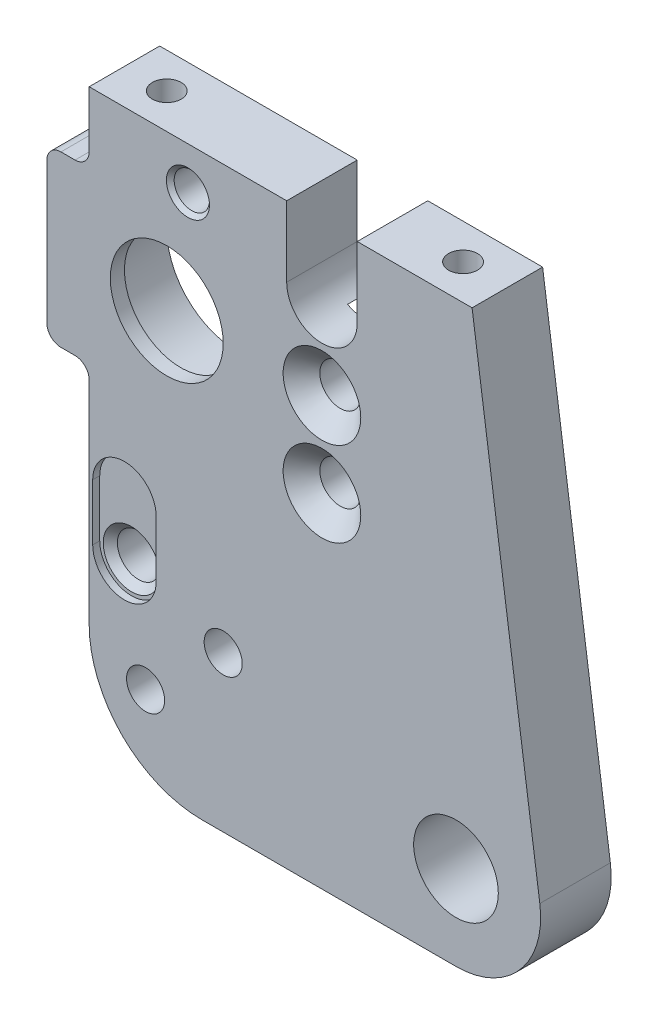
SolidWorks part; units mm, degrees
material "7075-T6, Plate (SS)"
ref_plane "前视基准面" through (0, 0, 0) normal (0, 0, 1) x (1, 0, 0)
ref_plane "上视基准面" through (0, 0, 0) normal (0, 1, 0) x (1, 0, 0)
ref_plane "右视基准面" through (0, 0, 0) normal (1, 0, 0) x (0, 0, -1)
sketch "草图1" plane through (0, 0, 0) normal (0, 0, 1) x (1, 0, 0)
  line L1 (0, 41) -> (34, 41)
  line L2 (0, 41) -> (0, 0)
  line L3 (0, 0) -> (34, 0)
  line L4 (34, 41) -> (34, 0)
  dimension "D1" = 34
  dimension "D2" = 41
  dimension "D3" = 90
extrude "拉伸1" add sketch "草图1" along normal blind 5
fillet "圆角1" radius 8 1 edges at (0, 0, 2.5)
sketch "草图2" plane through (0, 0, 5) normal (0, 0, 1) x (1, 0, 0)
  line L0 (0, 41) -> (0, 8) construction
  line L2 (8, 0) -> (34, 0) construction
  circle A0 centre (26, 6) radius 3
  dimension "D2" = 6
  dimension "D3" = 6
  dimension "D1" = 26
extrude "拉伸2" cut sketch "草图2" against normal up to surface (5 mm away) up to face at (14.8686, 17.6686, 0)
sketch "草图3" plane through (0, 0, 0) normal (0, 0, -1) x (-1, 0, 0)
  line L1 (0, 41) -> (0, 8) construction
  line L2 (-8, 0) -> (-34, 0) construction
  circle A0 centre (-5.5, 30) radius 4
  dimension "D1" = 8
  dimension "D3" = 5.5
  dimension "D2" = 30
extrude "拉伸3" cut sketch "草图3" against normal up to surface (5 mm away) up to face at (29, 6, 5)
sketch "草图4" plane through (0, 0, 0) normal (0, 0, -1) x (-1, 0, 0)
  circle A0 centre (-5.5, 30) radius 5
  dimension "D1" = 10
extrude "拉伸4" cut sketch "草图4" against normal blind 4
sketch "草图5" plane through (0, 41, 0) normal (0, 1, 0) x (1, 0, 0)
  line L0 (3, -2.5) -> (24, -2.5)
  line L1 (17, 0) -> (17, -2.5) construction
  line L2 (34, 0) -> (0, 0) construction
  line L3 (0, -5) -> (0, 0) construction
  dimension "D1" = 21
  dimension "D2" = 2.5
  dimension "D3" = 3
hole_wizard "M2.5 螺纹孔1" positions "3D草图1" profile "草图6" tap size "M2.5" standard "GB"
sketch3d "3D草图1"
  point P0 (3, 41, 2.5)
  point P3 (24, 41, 2.5)
sketch "草图6" plane through (3, 41, 2.5) normal (1, 0, 0) x (0, 0, 1)
  line L0 (0, 0) -> (0, 7.9659)
  line L1 (0, 7.9659) -> (1.025, 7.35)
  line L2 (1.025, 7.35) -> (1.025, 0)
  line L5 (1.025, 0) -> (0, 0)
  line L10 (0, 7.9659) -> (-1.025, 7.35) construction
  line L11 (0, -6.35) -> (0, 107.95) construction
  dimension "螺纹孔钻头直径" = 2.05
  dimension "螺纹孔钻头深度" = 7.35
  dimension "导头角度" = 118
cosmetic thread "孔螺蚊线1" parameters "D1"=6, "D2"=2.5
cosmetic thread "孔螺蚊线2" parameters "D1"=6, "D2"=2.5
chamfer "倒角1" [suppressed] distance 0.5 angle 45
chamfer "倒角2" [suppressed] distance 0.5 angle 45
sketch "草图7" plane through (0, 0, 0) normal (0, 0, -1) x (-1, 0, 0)
  line L0 (-8, 0) -> (-34, 0) construction
  line L1 (-26, 0) -> (-34, 0)
  line L2 (-31.9416, 6.835) -> (-27.14, 41)
  line L3 (-34, 41) -> (0, 41) construction
  line L4 (-34, 0) -> (-34, 41)
  line L5 (-34, 41) -> (-27.14, 41)
  arc A0 (-31.9416, 6.835) -> (-26, 0) centre (-26, 6) ccw
  dimension "D1" = 6
  dimension "D2" = 8
extrude "拉伸5" cut sketch "草图7" against normal blind 10
sketch "Sketch1" plane through (0, 0, 5) normal (0, 0, 1) x (1, 0, 0)
  line L0 (26, 0) -> (12, 0)
  line L1 (8, 0) -> (26, 0) construction
  line L2 (0, 12.9802) -> (0, 12)
  line L3 (0, 41) -> (0, 8) construction
  line L4 (26, 6) -> (29.4415, 1.0851) construction
  line L5 (29.4415, 1.0851) -> (0, 12.9802)
  arc A0 (26, 0) -> (31.9416, 6.835) centre (26, 6) ccw construction
  arc A1 (26, 0) -> (29.4415, 1.0851) centre (26, 6) ccw
  arc A2 (12, 0) -> (0, 12) centre (12, 12) cw
  dimension "D2" = 12
  dimension "D1" = 0
  dimension "D3" = 55
  dimension "D4" = 22
extrude "Extrude1" add sketch "Sketch1" against normal up to surface (5 mm away) up to face at (0.5, 30, 0)
sketch "草图8" plane through (0, 0, 5) normal (0, 0, 1) x (1, 0, 0)
  line L0 (8, 0) -> (26, 0) construction
  line L1 (0, 41) -> (0, 8) construction
  circle A0 centre (2.5, 13) radius 1.5
  dimension "D1" = 3
  dimension "D3" = 2.5
  dimension "D2" = 13
extrude "拉伸6" cut sketch "草图8" against normal blind 4.5
sketch "Sketch9" plane through (0, 0, 0.5) normal (0, 0, 1) x (1, 0, 0)
  line L0 (2.5, 13) -> (1.5, 13) construction
  circle A0 centre (1.5, 13) radius 0.5
  dimension "D2" = 1
  dimension "D1" = 1
extrude "Extrude5" cut sketch "Sketch9" against normal through all
sketch "草图9" plane through (0, 0, 5) normal (0, 0, 1) x (1, 0, 0)
  line L0 (2.5, 13) -> (2.5, 17) construction
  line L1 (0.25, 13) -> (0.25, 17)
  line L2 (4.75, 13) -> (4.75, 17)
  line L3 (0, 41) -> (0, 8) construction
  arc A0 (0.25, 13) -> (4.75, 13) centre (2.5, 13) ccw
  arc A1 (4.75, 17) -> (0.25, 17) centre (2.5, 17) ccw
  point P3 (2.5, 15)
  dimension "D1" = 0
  dimension "D2" = 4.5
  dimension "D3" = 4
extrude "拉伸7" cut sketch "草图9" against normal blind 0.5
chamfer "倒角3" distance 0.5 angle 45 1 edges at (4, 13, 4.5)
sketch "草图11" plane through (0, 0, 5) normal (0, 0, 1) x (1, 0, 0)
  line L0 (4, 19) -> (4, 7)
  line L2 (0, 41) -> (0, 8) construction
  line L3 (2.5, 13) -> (4, 13)
  line L4 (4, 13) -> (9.5, 13)
  dimension "D1" = 12
  dimension "D2" = 5.5
  dimension "D3" = 4
hole_wizard "M2.5 Tapped Hole1" [suppressed] positions "3D草图2" profile "草图12" tap size "M2.5" standard "GB"
sketch3d "3D草图2"
  point P3 (4, -31.5, 5)
  point P6 (9.5, -25.5, 5)
sketch "草图12" plane through (4, -31.5, 5) normal (1, 0, 0) x (0, -1, 0)
  line L0 (0, 0) -> (0, 6.9659)
  line L1 (0, 6.9659) -> (1.025, 6.35)
  line L2 (1.025, 6.35) -> (1.025, 0)
  line L5 (1.025, 0) -> (0, 0)
  line L10 (0, 6.9659) -> (-1.025, 6.35) construction
  line L11 (0, -6.35) -> (0, 107.95) construction
  dimension "螺纹孔钻头直径" = 2.05
  dimension "螺纹孔钻头深度" = 6.35
  dimension "导头角度" = 118
cosmetic thread "孔螺蚊线3" [suppressed] parameters "D1"=5, "D2"=2.5
cosmetic thread "孔螺蚊线4" [suppressed] parameters "D1"=5, "D2"=2.5
chamfer "倒角4" [suppressed] distance 0.2 angle 45
sketch "草图13" plane through (0, 0, 5) normal (0, 0, 1) x (1, 0, 0)
  line L0 (27.14, 41) -> (0, 41) construction
  line L1 (0, 41) -> (0, 8) construction
  circle A0 centre (20, 27) radius 4 construction
  circle A1 centre (16, 12.5) radius 4
  dimension "D1" = 8
  dimension "D2" = 14
  dimension "D3" = 20
  dimension "D4" = 16
  dimension "D5" = 28.5
sketch "Sketch2" plane through (0, 0, 0) normal (0, 0, -1) x (-1, 0, 0)
  line L1 (-13.5, 21.8) -> (-19.5, 21.8)
  line L2 (-13.5, 21.8) -> (-13.5, 33.8)
  line L3 (-13.5, 33.8) -> (-19.5, 33.8)
  line L4 (-19.5, 21.8) -> (-19.5, 33.8)
  line L6 (-16.5, 33.8) -> (-16.5, 21.8) construction
  line L7 (-19.5, 27.8) -> (-13.5, 27.8) construction
  circle A0 centre (-5.5, 30) radius 5 construction
  circle A1 centre (-5.5, 30) radius 5 construction
  dimension "D1" = 11
  dimension "D2" = 2.2
  dimension "D3" = 12
  dimension "D4" = 6
extrude "Extrude2" cut sketch "Sketch2" against normal blind 2
sketch "Sketch3" plane through (0, 0, 5) normal (0, 0, 1) x (1, 0, 0)
  line L0 (13.5, 33.8) -> (19.5, 33.8) construction
  line L1 (13.5, 33.8) -> (19.5, 33.8)
  line L2 (19.5, 21.8) -> (13.5, 21.8) construction
  line L3 (19.5, 21.8) -> (13.5, 21.8)
  line L4 (16.5, 33.8) -> (16.5, 30.3)
  line L5 (16.5, 30.3) -> (16.5, 24.3)
  line L6 (16.5, 24.3) -> (16.5, 21.8)
  dimension "D2" = 2.5
  dimension "D1" = 6
sketch "Sketch7" plane through (0, 0, 0) normal (0, 0, -1) x (-1, 0, 0)
  line L0 (-19.5, 33.8) -> (-19.5, 21.8) construction
  line L1 (-13.5, 21.8) -> (-13.5, 33.8) construction
  circle A0 centre (-19.5, 32.3) radius 1.5
  circle A1 centre (-13.5, 32.3) radius 1.5
  circle A2 centre (-19.5, 23.3) radius 1.5
  circle A3 centre (-13.5, 23.3) radius 1.5
  dimension "D1" = 3
extrude "Extrude3" cut sketch "Sketch7" against normal up to surface (2 mm away) up to face at (16.5, 27.8, 2)
sketch "Sketch8" plane through (0, 0, 0) normal (0, 0, -1) x (-1, 0, 0)
  line L0 (-14, 36) -> (-14, 41)
  line L1 (-27.14, 41) -> (0, 41) construction
  line L2 (-14, 41) -> (-19, 41)
  line L3 (-19, 41) -> (-19, 36)
  line L4 (0, 41) -> (0, 8) construction
  arc A0 (-19, 36) -> (-14, 36) centre (-16.5, 36) ccw
  dimension "D1" = 2.5
  dimension "D2" = 5
  dimension "D3" = 16.5
extrude "Extrude4" cut sketch "Sketch8" against normal through all
sketch "Sketch10" plane through (0, 0, 4.5) normal (0, 0, 1) x (1, 0, 0)
  circle A0 centre (2.5, 13) radius 1.5 construction
  circle A1 centre (2.5, 13) radius 1.5
extrude "Extrude6" cut sketch "Sketch10" against normal blind 10
sketch "Sketch11" plane through (0, 0, 0) normal (0, 0, 1) x (1, 0, 0)
  line L0 (4, 7) -> (4, 6)
  line L1 (4, 13) -> (9.5, 13) construction
  line L2 (4, 11) -> (9.5, 11)
  line L3 (4, 19) -> (4, 7) construction
  dimension "D1" = 7
  dimension "D2" = 5.5
  dimension "D3" = 5
hole_wizard "CBORE for M2.5 Hexagon socket head cap screws1" positions "3DSketch4" profile "Sketch12" counterbore size "M2.5" standard "GB" end condition through all
sketch3d "3DSketch4"
  point P0 (4, 6, 0)
  point P3 (9.5, 11, 0)
sketch "Sketch12" plane through (4, 6, 0) normal (1, 0, 0) x (0, 1, 0)
  line L0 (0, 0) -> (0, 5)
  line L1 (0, 5) -> (1.35, 5)
  line L3 (1.35, 5) -> (1.35, 2.5)
  line L4 (1.35, 2.5) -> (2.5, 2.5)
  line L5 (2.5, 2.5) -> (2.5, 0)
  line L7 (2.5, 0) -> (0, 0)
  line L11 (0, -6.35) -> (0, 107.95) construction
  dimension "Thru Hole Dia." = 2.7
  dimension "Thru Hole Depth" = 5
  dimension "C'Bore Dia." = 5
  dimension "C'Bore Depth" = 2.5
sketch "草图21" plane through (0, 0, 0) normal (-1, 0, 0) x (0, 0, 1)
  line L0 (0, 36) -> (5, 36)
  line L3 (5, 41) -> (0, 41) construction
  line L4 (0, 41) -> (0, 8) construction
  line L5 (5, 41) -> (5, 8) construction
  line L6 (0, 24) -> (5, 24)
  line L7 (0, 36) -> (0, 24)
  line L8 (5, 36) -> (5, 24)
  dimension "D1" = 12
  dimension "D2" = 5
sketch "草图24" plane through (0, 0, 5) normal (0, 0, 1) x (1, 0, 0)
  line L0 (0, 41) -> (0, 8) construction
  line L1 (19.5, 21.8) -> (13.5, 21.8) construction
  point P0 (16.5, 30.3)
  point P1 (16.5, 24.3)
  dimension "D1" = 16.5
  dimension "D2" = 16.5
  dimension "D3" = 6
  dimension "D4" = 2.5
hole_wizard "M2.5 平头机械螺钉的锥形沉头孔1" positions "3D草图6" profile "草图27" countersink size "M2.5" standard "ANSI Metric" end condition through all
sketch3d "3D草图6"
  point P0 (16.5, 30.3, 5)
  point P3 (16.5, 24.3, 5)
sketch "草图27" plane through (16.5, 30.3, 5) normal (1, 0, 0) x (0, -1, 0)
  line L0 (0, 0) -> (0, 5)
  line L1 (0, 5) -> (1.45, 5)
  line L2 (1.45, 5) -> (1.45, 1.3)
  line L3 (1.45, 1.3) -> (2.75, 0)
  line L5 (2.75, 0) -> (0, 0)
  line L6 (-1.45, 1.3) -> (-2.75, 0) construction
  line L11 (0, -6.35) -> (0, 107.95) construction
  dimension "通孔孔直径" = 2.9
  dimension "通孔孔深度" = 5
  dimension "近端锥形沉头孔直径" = 5.5
  dimension "近端锥形沉头孔角度" = 90
extrude "凸台-拉伸1" add sketch "草图21" along normal blind 3 contours L0 L8 L6 L7
fillet "圆角2" radius 1 4 edges at (0, 24, 2.5) (-3, 24, 2.5) (-3, 36, 2.5) (0, 36, 2.5)
sketch "草图28" plane through (0, 0, 5) normal (0, 0, 1) x (1, 0, 0)
  line L0 (0, 41) -> (0, 37) construction
  line L1 (3, 41) -> (24, 41) construction
  point P0 (7, 38)
  dimension "D1" = 7
  dimension "D2" = 3
hole_wizard "M3x0.5 螺纹孔1" positions "3D草图7" profile "草图29" tap size "M3x0.5" standard "ANSI Metric" end condition through all
sketch3d "3D草图7"
  point P0 (7, 38, 5)
sketch "草图29" plane through (7, 38, 5) normal (1, 0, 0) x (0, -1, 0)
  line L0 (0, 0) -> (0, 5)
  line L1 (0, 5) -> (1.25, 5)
  line L2 (1.25, 5) -> (1.25, 0.275)
  line L3 (1.25, 0.275) -> (1.525, 0)
  line L5 (1.525, 0) -> (0, 0)
  line L6 (-1.25, 0.275) -> (-1.525, 0) construction
  line L11 (0, -6.35) -> (0, 107.95) construction
  dimension "通孔螺纹孔钻头直径" = 2.5
  dimension "通孔螺纹孔钻头深度" = 5
  dimension "近端锥形沉头孔直径" = 3.05
  dimension "近端锥形沉头孔角度" = 90
cosmetic thread "孔螺蚊线5" parameters "D2"=3
